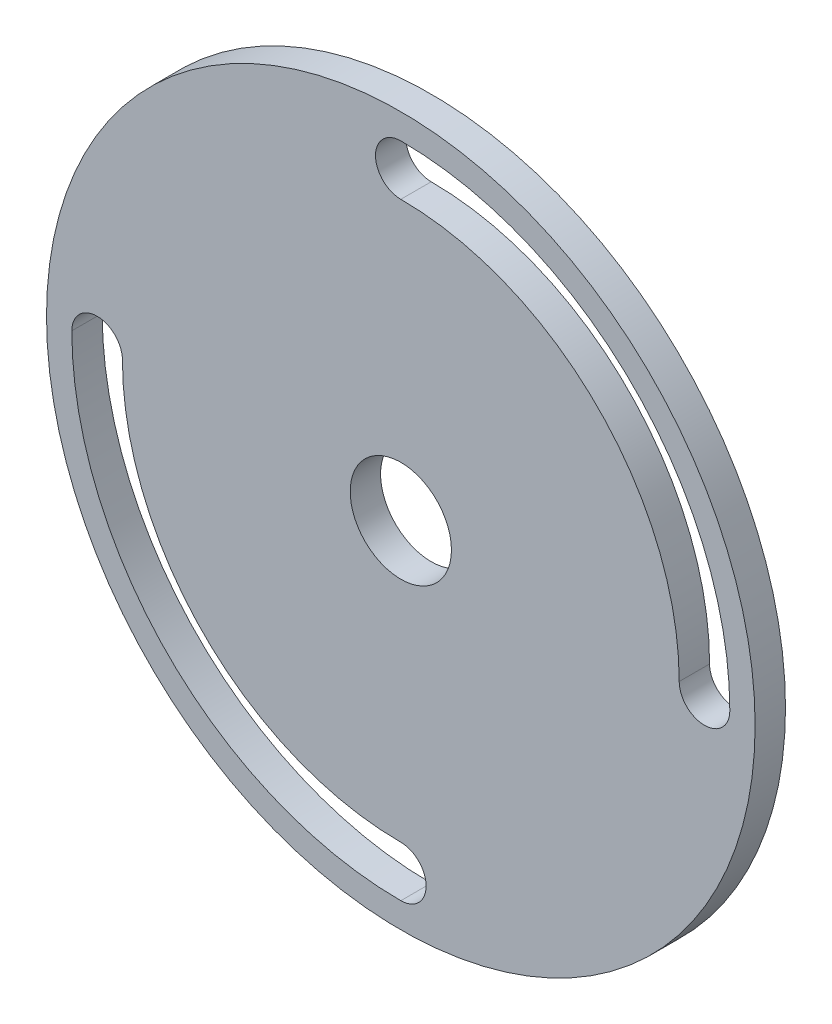
SolidWorks part; units mm, degrees
ref_plane "정면" through (0, 0, 0) normal (0, 0, 1) x (1, 0, 0)
ref_plane "윗면" through (0, 0, 0) normal (0, 1, 0) x (1, 0, 0)
ref_plane "우측면" through (0, 0, 0) normal (1, 0, 0) x (0, 0, -1)
sketch "스케치1" plane through (0, 0, 0) normal (0, 0, 1) x (1, 0, 0)
  line L0 (0, 65.3097) -> (0, -65.3097) construction
  line L1 (-109.2501, 0) -> (109.2501, 0) construction
  line L2 (15, 25.9808) -> (0, 0) construction
  circle A0 centre (0, 0) radius 5
  circle A1 centre (0, 0) radius 30 construction
  circle A2 centre (0, 0) radius 35
  circle A29 centre (0, 0) radius 32.5
  circle A30 centre (0, 0) radius 27.5
  circle A31 centre (30, 0) radius 2.5
  arc A32 (0, 32.5) -> (0, 27.5) centre (0, 30) ccw
  arc A33 (0, -32.5) -> (0, -27.5) centre (0, -30) cw
  circle A34 centre (-30, 0) radius 2.5
  circle A35 centre (0, -30) radius 2.5
  point P5 (0, 0)
  point P6 (0, 0)
  point P39 (0, 0)
  point P44 (0, 0)
  dimension "D1" = 10
  dimension "D2" = 60
  dimension "D3" = 70
  dimension "D4" = 65
  dimension "D7" = 55
  dimension "D8" = 2.5
  dimension "D6" = 30
sketch "스케치4" plane through (0, 0, 0) normal (1, 0, 0) x (0, 0, -1)
  line L0 (0, -6) -> (0, 6)
  line L1 (0, 65.3097) -> (0, -65.3097) construction
  line L5 (0, -6) -> (25, -6)
  line L6 (25, -6) -> (25, 6)
  line L7 (25, 6) -> (0, 6)
  point P4 (0, 0)
  dimension "D1" = 12
  dimension "D2" = 25
sketch "스케치5" plane through (0, 0, 0) normal (0, 1, 0) x (1, 0, 0)
  line L0 (-10, 0) -> (10, 0)
  line L1 (-109.2501, 0) -> (109.2501, 0) construction
  line L2 (0, 0) -> (0, 14) construction
  line L3 (-10, 0) -> (-5.2626, 15.5983)
  line L4 (10, 0) -> (5.2626, 15.5983)
  circle A0 centre (0, 14) radius 2.5
  arc A2 (-5.2626, 15.5983) -> (5.2626, 15.5983) centre (0, 14) cw
  point P4 (0, 0)
  dimension "D3" = 5
  dimension "D4" = 5.5
  dimension "D1" = 20
  dimension "D2" = 14
extrude "보스-돌출1" add sketch "스케치1" along normal blind 3 contours A30 A0 | A34 A30 A32 A29 | A35 A29 A31 A30 | A2 A29
